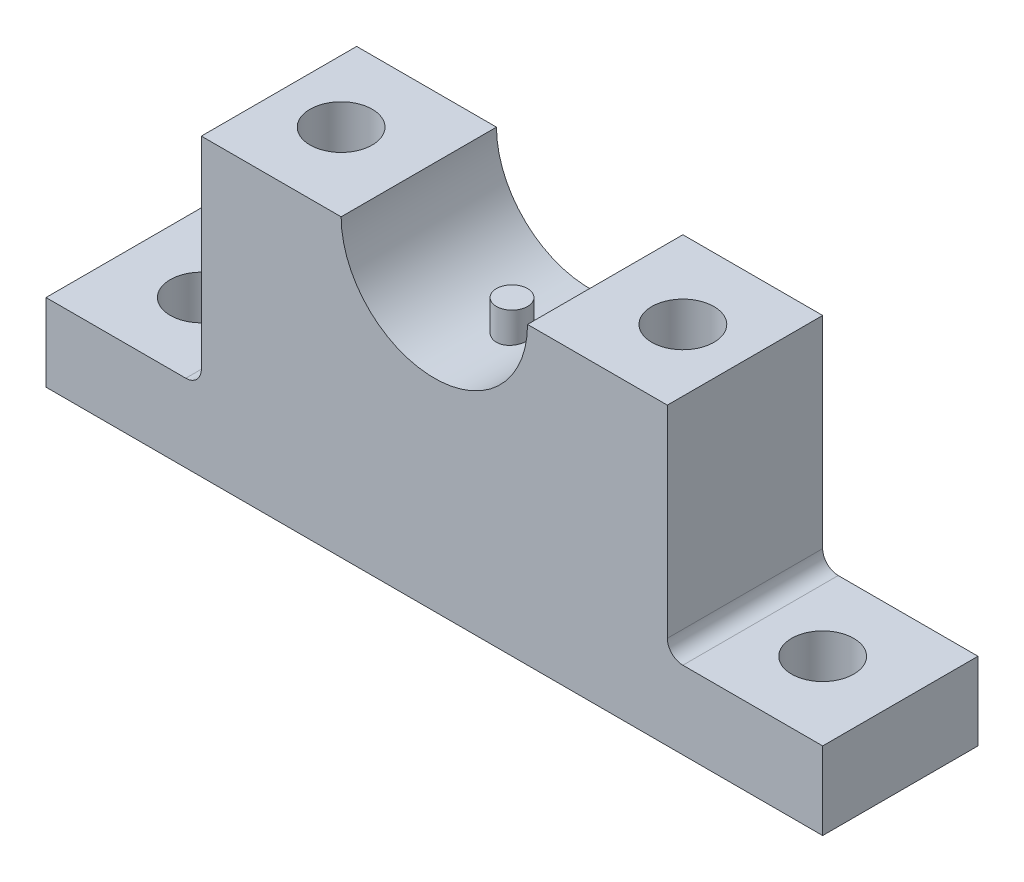
SolidWorks part; units mm, degrees
ref_plane "Front Plane" through (0, 0, 0) normal (0, 0, 1) x (1, 0, 0)
ref_plane "Top Plane" through (0, 0, 0) normal (0, 1, 0) x (1, 0, 0)
ref_plane "Right Plane" through (0, 0, 0) normal (1, 0, 0) x (0, 0, -1)
sketch "Sketch1" plane through (0, 0, 0) normal (0, 0, 1) x (1, 0, 0)
  line L0 (-6, 0) -> (-15, 0)
  line L1 (-15, 0) -> (-15, -13)
  line L2 (-16, -14) -> (-25, -14)
  line L3 (-25, -14) -> (-25, -19)
  line L4 (-25, -19) -> (25, -19)
  line L5 (25, -19) -> (25, -14)
  line L6 (25, -14) -> (16, -14)
  line L7 (15, -13) -> (15, 0)
  line L8 (15, 0) -> (6, 0)
  line L9 (0, 16.2727) -> (0, -16.2727) construction
  arc A0 (-6, 0) -> (6, 0) centre (0, 0) ccw
  arc A1 (16, -14) -> (15, -13) centre (16, -13) cw
  arc A2 (-15, -13) -> (-16, -14) centre (-16, -13) cw
  point P14 (0, 0)
  point P17 (15, -14)
  dimension "D1" = 6
  dimension "D8" = 1
  dimension "D2" = 15
  dimension "D3" = 14
  dimension "D4" = 5
  dimension "D5" = 14
  dimension "D6" = 5
  dimension "D7" = 25
extrude "Boss-Extrude1" add sketch "Sketch1" along normal mid plane 10
sketch "Sketch2" plane through (0, -14, 0) normal (0, 1, 0) x (1, 0, 0)
  circle A0 centre (-20, 0) radius 2
  circle A1 centre (20, 0) radius 2
  dimension "D1" = 4
  dimension "D2" = 20
  dimension "D3" = 20
extrude "Cut-Extrude1" cut sketch "Sketch2" against normal through all
sketch "Sketch3" plane through (0, 0, 0) normal (0, 1, 0) x (1, 0, 0)
  circle A0 centre (-11, 0) radius 2
  circle A1 centre (11, 0) radius 2
  dimension "D1" = 4
  dimension "D2" = 11
  dimension "D3" = 11
extrude "Cut-Extrude2" cut sketch "Sketch3" against normal blind 6
sketch "Sketch4" plane through (0, 0, 0) normal (0, 1, 0) x (1, 0, 0)
  circle A0 centre (0, 0) radius 1
  dimension "D1" = 2
extrude "Cut-Extrude3" cut sketch "Sketch4" against normal blind 8
ref_plane "Plane1" through (0, -4, 0) normal (0, 1, 0) x (1, 0, 0)
sketch "Sketch5" plane through (0, -4, 0) normal (0, 1, 0) x (1, 0, 0)
  circle A0 centre (0, 0) radius 1
extrude "Boss-Extrude3" add sketch "Sketch5" against normal up to surface (2 mm away) separate body
